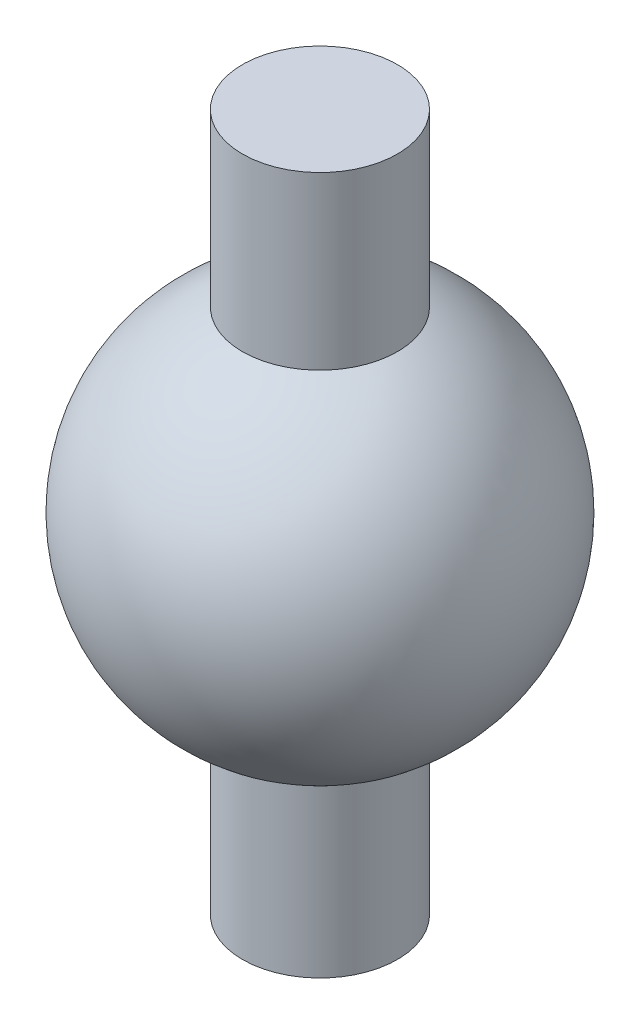
SolidWorks part; units mm, degrees
ref_plane "Front Plane" through (0, 0, 0) normal (0, 0, 1) x (1, 0, 0)
ref_plane "Top Plane" through (0, 0, 0) normal (0, 1, 0) x (1, 0, 0)
ref_plane "Right Plane" through (0, 0, 0) normal (1, 0, 0) x (0, 0, -1)
sketch "Sketch2" plane through (0, 0, 0) normal (1, 0, 0) x (0, 0, -1)
  line L0 (-88.9642, 144.2999) -> (-88.9642, 99.2999) construction
  line L1 (-32.9, 99.2999) -> (-93.4757, 99.2999) construction
  line L3 (-83.9642, 144.2999) -> (-93.9642, 144.2999)
  line L4 (-83.9642, 99.2999) -> (-93.9642, 99.2999)
  line L5 (-83.9642, 144.2999) -> (-83.9642, 99.2999)
  line L6 (-93.9642, 144.2999) -> (-93.9642, 99.2999)
  circle A0 centre (-88.9642, 121.7999) radius 12.5
  point P5 (-88.9642, 144.2999)
  point P8 (-88.9642, 99.2999)
  dimension "D2" = 25
  dimension "D1" = 45
  dimension "D3" = 10
revolve "Revolve1" add sketch "Sketch2" angle 360 about L0
